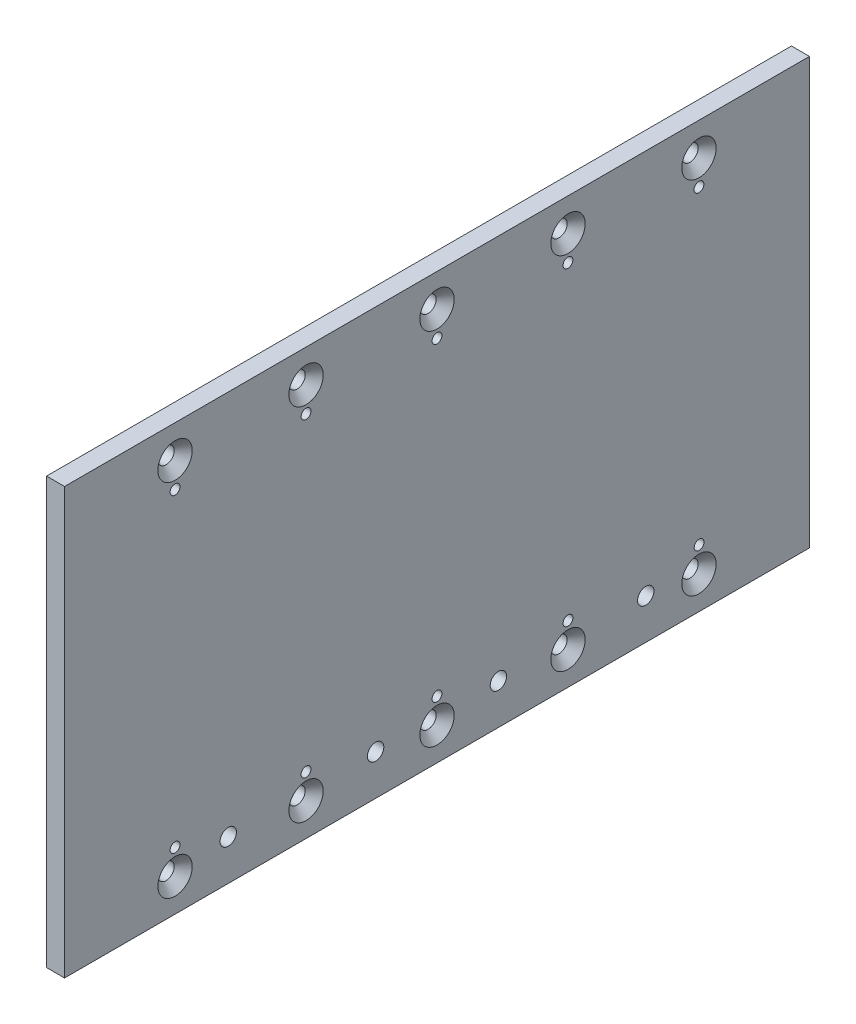
SolidWorks part; units mm, degrees
material "Aluminum"
ref_plane "Front Plane" through (0, 0, 0) normal (0, 0, 1) x (1, 0, 0)
ref_plane "Top Plane" through (0, 0, 0) normal (0, 1, 0) x (1, 0, 0)
ref_plane "Right Plane" through (0, 0, 0) normal (1, 0, 0) x (0, 0, -1)
sketch "Sketch1" plane through (0, 0, 0) normal (1, 0, 0) x (0, 0, -1)
  line L1 (113.75, -65) -> (-113.75, -65)
  line L2 (113.75, -65) -> (113.75, 65)
  line L3 (113.75, 65) -> (-113.75, 65)
  line L4 (-113.75, -65) -> (-113.75, 65)
  line L5 (113.75, -65) -> (-113.75, 65) construction
  line L6 (113.75, 65) -> (-113.75, -65) construction
  point P0 (0, 0)
  dimension "D1" = 227.5
  dimension "D2" = 130
extrude "Boss-Extrude1" add sketch "Sketch1" along normal blind 5.5
hole_wizard "CSK for M5 Hex Socket Countersunk Cap Screw1" positions "Sketch6" profile "Sketch5" countersink size "M5" standard "ISO" end condition through all
sketch "Sketch6" plane through (5.5, 0, 0) normal (1, 0, 0) x (0, 0, -1)
  point P0 (80, 55)
  point P3 (40, 55)
  point P6 (0, 55)
  point P8 (-40, 55)
  point P11 (-80, 55)
  point P14 (-80, -55)
  point P17 (-40, -55)
  point P20 (0, -55)
  point P23 (40, -55)
  point P26 (80, -55)
sketch "Sketch5" plane through (5.5, 55, -80) normal (0, 1, 0) x (0, 0, -1)
  line L0 (0, 0) -> (0, 5.5)
  line L1 (0, 5.5) -> (2.5, 5.5)
  line L2 (2.5, 5.5) -> (2.5, 2.75)
  line L3 (2.5, 2.75) -> (5.25, 0)
  line L5 (5.25, 0) -> (0, 0)
  line L6 (-2.5, 2.75) -> (-5.25, 0) construction
  line L11 (0, -6.35) -> (0, 107.95) construction
  dimension "Thru Hole Dia." = 5
  dimension "Thru Hole Depth" = 5.5
  dimension "Near C'Sink Dia." = 10.5
  dimension "Near C'Sink Angle" = 90
hole_wizard "Tap Drill for M5x0.8 Tap1" positions "Sketch8" profile "Sketch7" hole size "M5x0.8" standard "ANSI Metric" end condition through all
sketch "Sketch8" plane through (5.5, 0, 0) normal (1, 0, 0) x (0, 0, -1)
  point P0 (-63.75, -52.6538)
  point P3 (-18.75, -52.6538)
  point P6 (18.75, -52.6538)
  point P9 (63.75, -52.6538)
sketch "Sketch7" plane through (5.5, -52.6538, 63.75) normal (0, 1, 0) x (0, 0, -1)
  line L0 (0, 0) -> (0, 5.5)
  line L1 (0, 5.5) -> (2.5, 5.5)
  line L2 (2.5, 5.5) -> (2.5, 0)
  line L5 (2.5, 0) -> (0, 0)
  line L11 (0, -6.35) -> (0, 107.95) construction
  dimension "Thru Hole Dia." = 5
  dimension "Thru Hole Depth" = 5.5
sketch "Sketch9" plane through (0, 0, 0) normal (-1, 0, 0) x (0, 0, 1)
  circle A0 centre (-80.0458, -47.3325) radius 1.5
  circle A1 centre (-40, -47.3325) radius 1.5
  circle A2 centre (0, -47.3325) radius 1.5
  circle A3 centre (40, -47.3325) radius 1.5
  circle A4 centre (80, -47.3325) radius 1.5
  dimension "D1" = 3
extrude "Cut-Extrude1" cut sketch "Sketch9" against normal blind 29
sketch "Sketch10" plane through (0, 0, 0) normal (-1, 0, 0) x (0, 0, 1)
  circle A0 centre (-80, 47.3325) radius 1.5
  circle A1 centre (-40, 47.3325) radius 1.5
  circle A2 centre (0, 47.3325) radius 1.5
  circle A3 centre (40, 47.3325) radius 1.5
  circle A4 centre (80, 47.3325) radius 1.5
extrude "Cut-Extrude2" cut sketch "Sketch10" against normal blind 29
